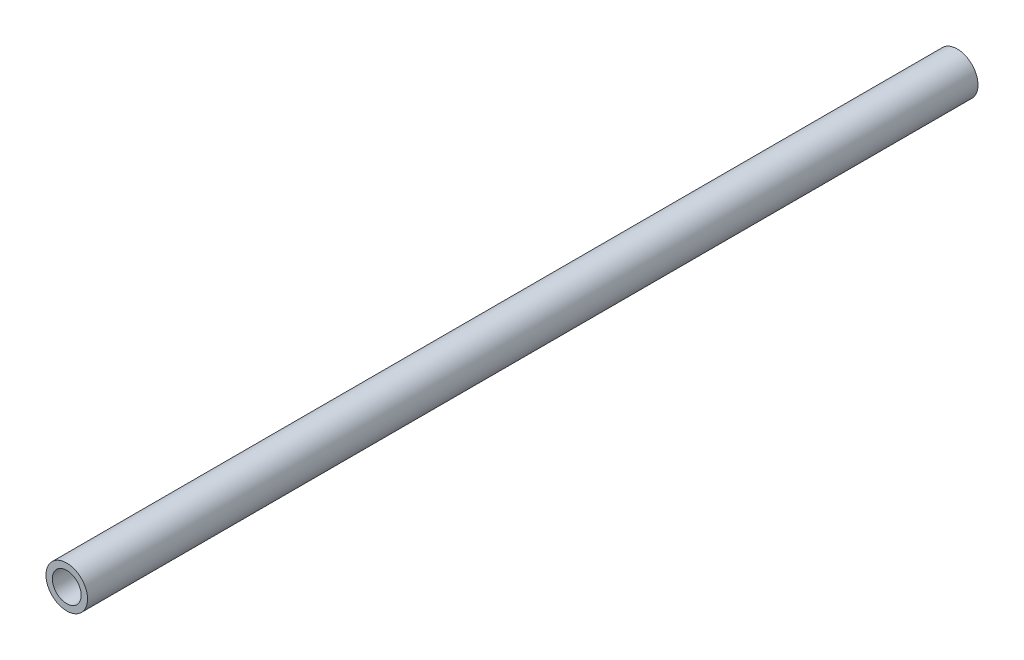
SolidWorks part; units mm, degrees
material "Thornel Mat VMA"
ref_plane "Front Plane" through (0, 0, 0) normal (0, 0, 1) x (1, 0, 0)
ref_plane "Top Plane" through (0, 0, 0) normal (0, 1, 0) x (1, 0, 0)
ref_plane "Right Plane" through (0, 0, 0) normal (1, 0, 0) x (0, 0, -1)
sketch "Sketch1" plane through (0, 0, 0) normal (0, 0, 1) x (1, 0, 0)
  circle A0 centre (0, 0) radius 4.572 construction
  circle A1 centre (0, 0) radius 3.175 construction
  point P4 (3.175, 0)
  point P5 (4.572, 0)
  dimension "OD" = 9.144
  dimension "ID" = 6.35
  dimension "Wall Thickness" = 1.397
sketch "Sketch2" plane through (0, 0, 0) normal (1, 0, 0) x (0, 0, -1)
  line L0 (-97.917, 0) -> (97.917, 0) construction
  line L1 (-97.917, -4.572) -> (-97.917, 4.572) construction
  line L2 (-97.917, 4.572) -> (97.917, 4.572) construction
  line L3 (97.917, -4.572) -> (97.917, 4.572) construction
  line L5 (-97.917, -4.572) -> (97.917, -4.572) construction
  point P0 (-88.773, 0)
  point P3 (0, 0)
  point P7 (0, 4.572)
  point P8 (88.773, 0)
  point P11 (-97.917, 0)
  point P13 (97.917, 0)
  dimension "Length" = 195.834
  dimension "D1" = 9.144
  dimension "D2" = 9.144
sketch "Sketch3" plane through (0, 0, 0) normal (0, 0, 1) x (1, 0, 0)
  circle A0 centre (0, 0) radius 3.175 construction
  circle A1 centre (0, 0) radius 4.572 construction
  circle A2 centre (0, 0) radius 3.175
  circle A3 centre (0, 0) radius 4.572
extrude "Boss-Extrude1" add sketch "Sketch3" along normal up to vertex (97.917 mm away) and the other way up to vertex (97.917 mm away) up to point (0, 0, 97.917) other way up to point (0, 0, -97.917)
equation "\"D1@Sketch2\"=\"OD@Sketch1\""
equation "\"D2@Sketch2\"=\"D1@Sketch2\""
